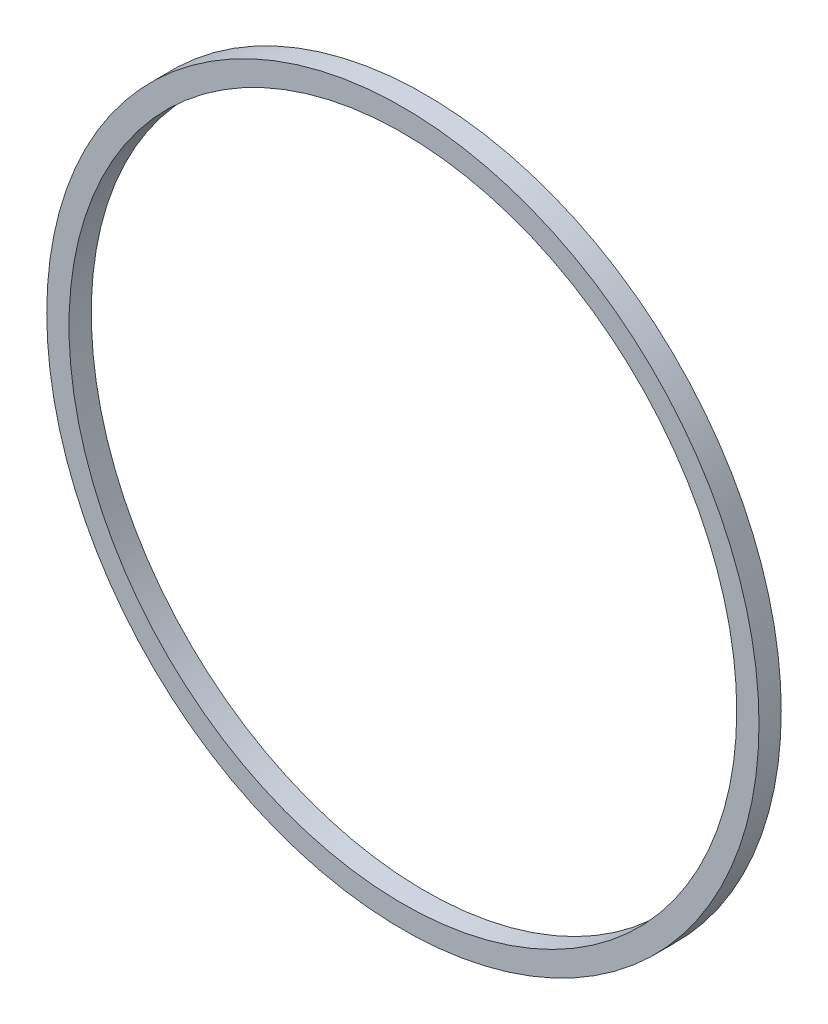
SolidWorks part; units mm, degrees
ref_plane "前视基准面" through (0, 0, 0) normal (0, 0, 1) x (1, 0, 0)
ref_plane "上视基准面" through (0, 0, 0) normal (0, 1, 0) x (1, 0, 0)
ref_plane "右视基准面" through (0, 0, 0) normal (1, 0, 0) x (0, 0, -1)
other "Configuration Table"
sketch "草图1" plane through (0, 0, 0) normal (0, 0, 1) x (1, 0, 0)
  circle A0 centre (0, 0) radius 15
  circle A1 centre (0, 0) radius 16
  dimension "D1" = 30
  dimension "D2" = 32
extrude "凸台-拉伸1" add sketch "草图1" along normal blind 1
